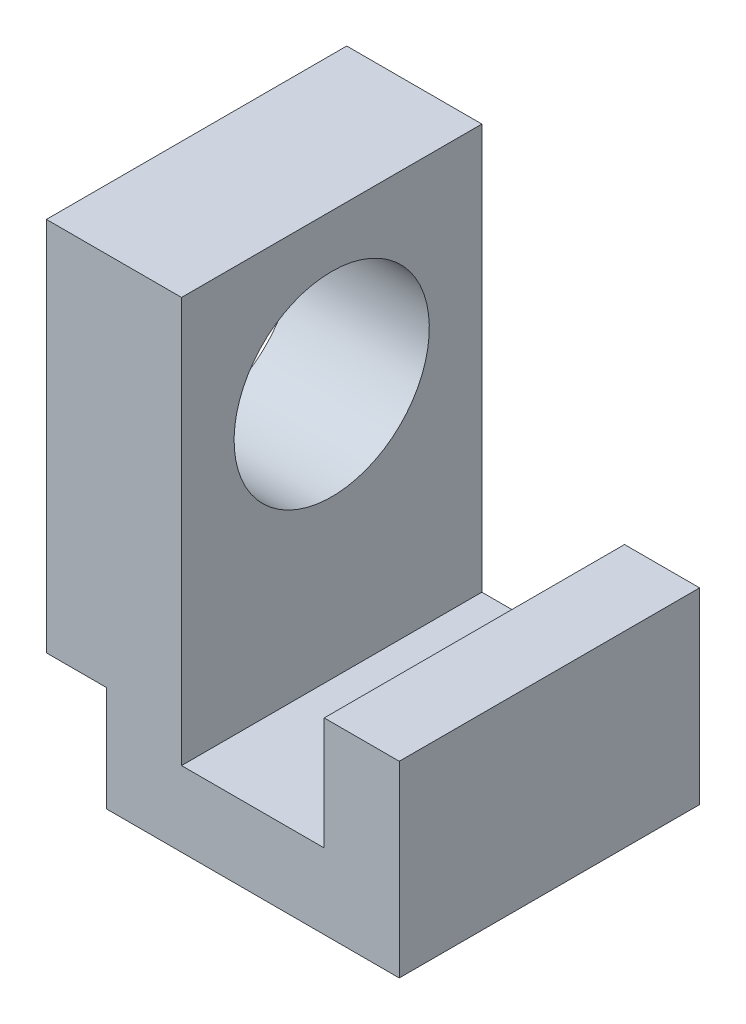
SolidWorks part; units mm, degrees
ref_plane "Front Plane" through (0, 0, 0) normal (0, 0, 1) x (1, 0, 0)
ref_plane "Top Plane" through (0, 0, 0) normal (0, 1, 0) x (1, 0, 0)
ref_plane "Right Plane" through (0, 0, 0) normal (1, 0, 0) x (0, 0, -1)
sketch "Sketch1" plane through (0, 0, 0) normal (0, 0, 1) x (1, 0, 0)
  line L0 (0, 0) -> (0, 14)
  line L1 (0, 14) -> (-8, 14)
  line L2 (-8, 14) -> (-8, 64)
  line L3 (-8, 64) -> (10, 64)
  line L4 (10, 64) -> (10, 10)
  line L5 (10, 10) -> (29, 10)
  line L6 (29, 10) -> (29, 25)
  line L7 (29, 25) -> (39, 25)
  line L8 (39, 25) -> (39, 0)
  line L9 (39, 0) -> (0, 0)
  point P11 (34, 25)
  dimension "D1" = 8
  dimension "D2" = 14
  dimension "D3" = 64
  dimension "D4" = 10
  dimension "D5" = 10
  dimension "D6" = 39
  dimension "D7" = 18
  dimension "D8" = 25
extrude "Boss-Extrude1" add sketch "Sketch1" along normal mid plane 40
sketch "Sketch2" plane through (10, 0, 0) normal (1, 0, 0) x (0, 0, -1)
  line L0 (-20, 10) -> (-20, 64) construction
  line L1 (-20, 10) -> (20, 10) construction
  circle A0 centre (0, 44) radius 13
  point P2 (0, 0)
  point P7 (0, 0)
  dimension "D1" = 26
  dimension "D2" = 20
  dimension "D3" = 34
extrude "Cut-Extrude1" cut sketch "Sketch2" against normal blind 40
